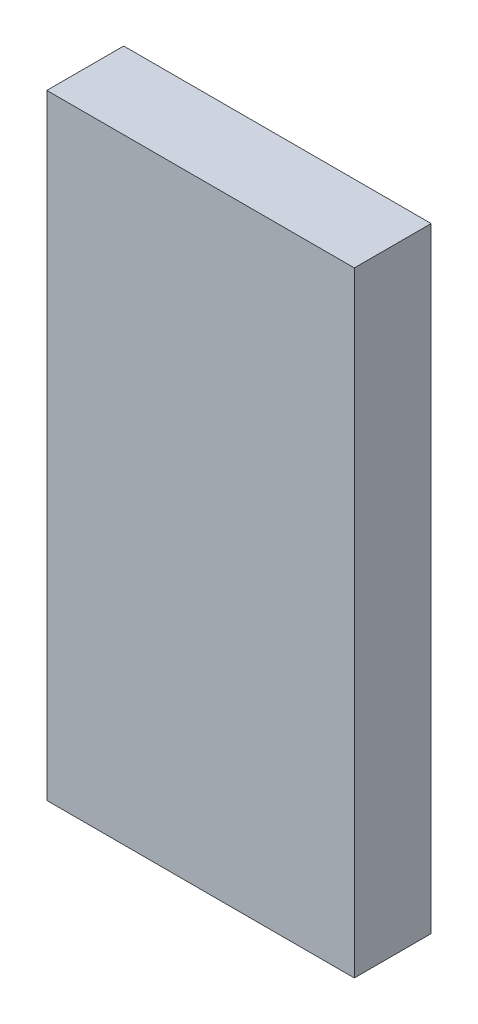
SolidWorks part; units mm, degrees
ref_plane "Front Plane" through (0, 0, 0) normal (0, 0, 1) x (1, 0, 0)
ref_plane "Top Plane" through (0, 0, 0) normal (0, 1, 0) x (1, 0, 0)
ref_plane "Right Plane" through (0, 0, 0) normal (1, 0, 0) x (0, 0, -1)
sketch "Sketch1" plane through (0, 0, 0) normal (0, 0, 1) x (1, 0, 0)
  line L1 (0, 0) -> (12.7, 0)
  line L2 (0, 0) -> (0, 25.4)
  line L3 (0, 25.4) -> (12.7, 25.4)
  line L4 (12.7, 0) -> (12.7, 25.4)
  dimension "D1" = 12.7
  dimension "D2" = 25.4
extrude "Boss-Extrude1" add sketch "Sketch1" along normal blind 3.175
sketch "Sketch2" plane through (0, 25.4, 0) normal (0, 1, 0) x (1, 0, 0)
  line L1 (0, 0) -> (12.7, 0)
  line L2 (0, 0) -> (0, -3.175)
  line L3 (0, -3.175) -> (12.7, -3.175)
  line L4 (12.7, 0) -> (12.7, -3.175)
